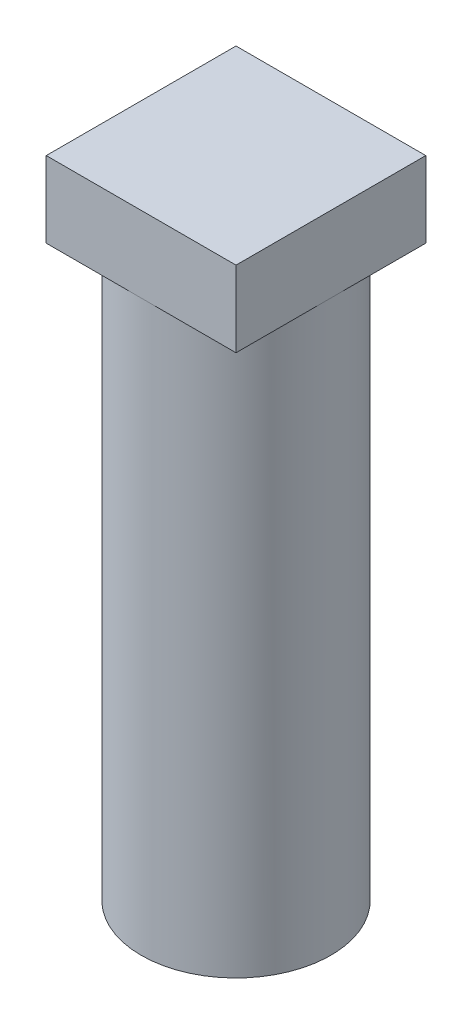
SolidWorks part; units mm, degrees
ref_plane "Front Plane" through (0, 0, 0) normal (0, 0, 1) x (1, 0, 0)
ref_plane "Top Plane" through (0, 0, 0) normal (0, 1, 0) x (1, 0, 0)
ref_plane "Right Plane" through (0, 0, 0) normal (1, 0, 0) x (0, 0, -1)
sketch "Sketch1" plane through (0, 0, 0) normal (0, 1, 0) x (1, 0, 0)
  circle A0 centre (0, 0) radius 2.5
extrude "Boss-Extrude1" add sketch "Sketch1" along normal blind 15
sketch "Sketch2" plane through (0, 15, 0) normal (0, 1, 0) x (1, 0, 0)
  line L1 (-2.5, 2.5) -> (2.5, 2.5)
  line L2 (-2.5, 2.5) -> (-2.5, -2.5)
  line L3 (-2.5, -2.5) -> (2.5, -2.5)
  line L4 (2.5, 2.5) -> (2.5, -2.5)
  line L5 (-2.5, 2.5) -> (2.5, -2.5) construction
  line L6 (-2.5, -2.5) -> (2.5, 2.5) construction
  point P0 (0, 0)
extrude "Boss-Extrude2" add sketch "Sketch2" along normal blind 2
